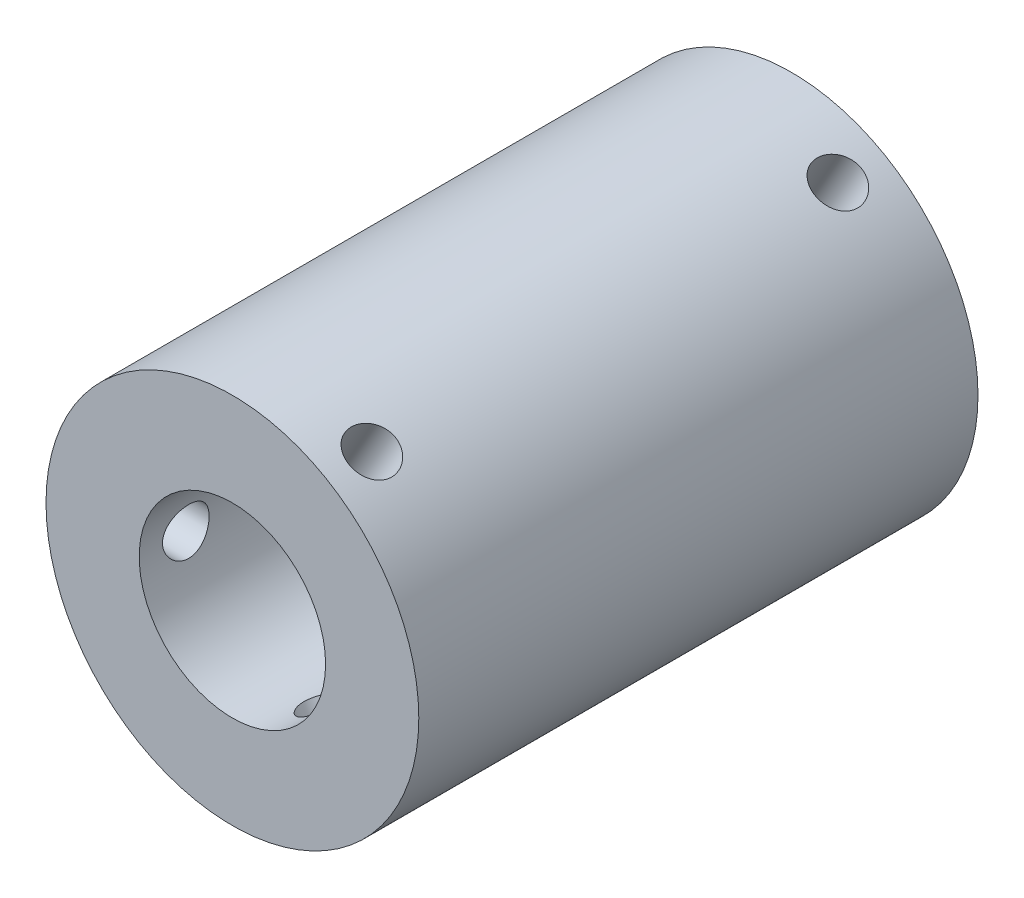
SolidWorks part; units mm, degrees
material "1060 Alloy"
ref_plane "Front Plane" through (0, 0, 0) normal (0, 0, 1) x (1, 0, 0)
ref_plane "Top Plane" through (0, 0, 0) normal (0, 1, 0) x (1, 0, 0)
ref_plane "Right Plane" through (0, 0, 0) normal (1, 0, 0) x (0, 0, -1)
sketch "Sketch1" plane through (0, 0, 0) normal (0, 0, 1) x (1, 0, 0)
  circle A0 centre (0, 0) radius 12.7
  dimension "D1" = 25.4
extrude "Boss-Extrude1" add sketch "Sketch1" along normal mid plane 38.1
sketch "Sketch2" plane through (0, 0, 19.05) normal (0, 0, 1) x (1, 0, 0)
  circle A0 centre (0, 0) radius 6.35
  dimension "D1" = 12.7
extrude "Cut-Extrude1" cut sketch "Sketch2" against normal blind 19.05
sketch "Sketch3" plane through (0, 0, -19.05) normal (0, 0, -1) x (-1, 0, 0)
  circle A0 centre (0, 0) radius 3.175
  dimension "D1" = 6.35
extrude "Cut-Extrude2" cut sketch "Sketch3" against normal blind 19.05
sketch "Sketch4" plane through (0, 0, 0) normal (1, 0, 0) x (0, 0, -1)
  line L0 (15.875, 0) -> (19.05, 0) construction
  line L1 (19.05, -12.7) -> (19.05, 12.7) construction
  line L2 (-15.875, 0) -> (-19.05, 0) construction
  line L3 (-19.05, 12.7) -> (-19.05, -12.7) construction
  circle A0 centre (15.875, 0) radius 1.5875
  circle A1 centre (-15.875, 0) radius 1.5875
  dimension "D1" = 3.175
  dimension "D2" = 3.175
extrude "Cut-Extrude3" cut sketch "Sketch4" against normal blind 19.05
pattern_circular "CirPattern1" count 3 every 120 about axis through (0, 0, 19.05) along (0, 0, -1) of "Cut-Extrude3"
